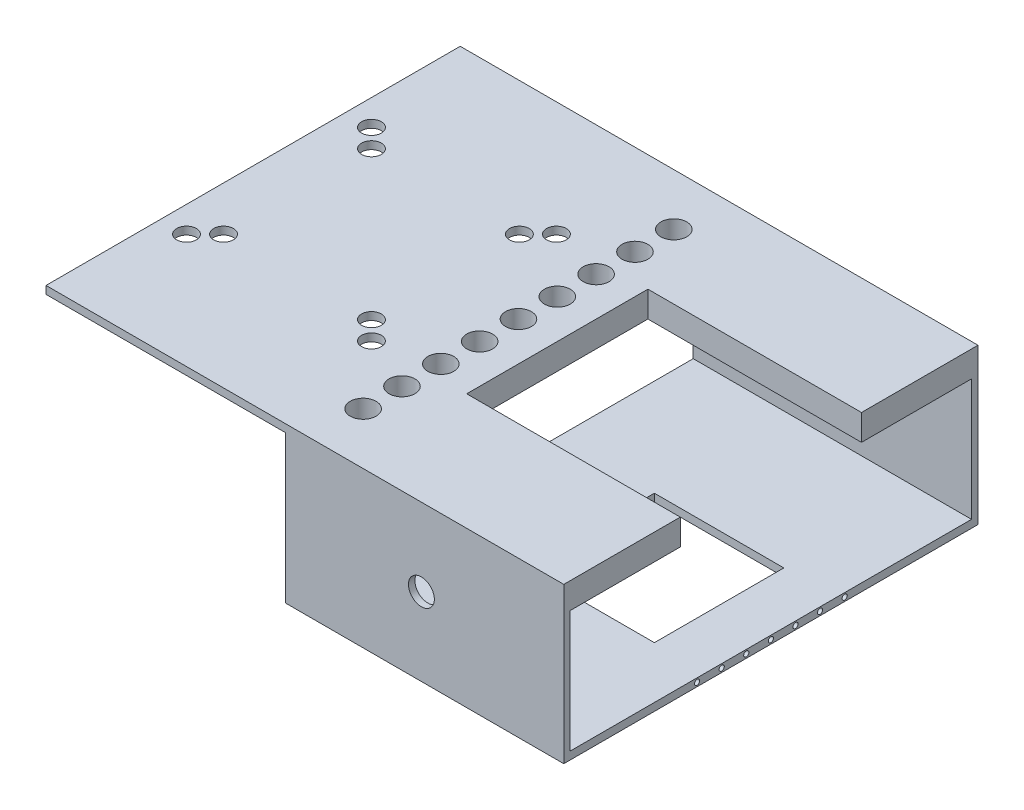
SolidWorks part; units mm, degrees
material "6063-T6"
ref_plane "前视基准面" through (0, 0, 0) normal (0, 0, 1) x (1, 0, 0)
ref_plane "上视基准面" through (0, 0, 0) normal (0, 1, 0) x (1, 0, 0)
ref_plane "右视基准面" through (0, 0, 0) normal (1, 0, 0) x (0, 0, -1)
other "Configuration Table"
sketch "草图1" plane through (0, 0, 0) normal (0, 1, 0) x (1, 0, 0)
  line L7 (-200, 160) -> (200, 160)
  line L8 (-200, 160) -> (-200, -160)
  line L9 (-200, -160) -> (200, -160)
  line L10 (200, 160) -> (200, -160)
extrude "凸台-拉伸7" add sketch "草图1" along normal blind 120
sketch "草图6" plane through (0, 120, 0) normal (0, 1, 0) x (1, 0, 0)
  circle A0 centre (-180, -71.4375) radius 7.62
  circle A1 centre (-165.7125, 57.1733) radius 7.62
  circle A2 centre (-165.7125, -57.1267) radius 7.62
  circle A3 centre (-180, 71.4375) radius 7.62
  circle A4 centre (-37.125, 71.4375) radius 7.62
  circle A5 centre (-51.4125, 57.1267) radius 7.62
  circle A6 centre (-51.4125, -57.1733) radius 7.62
  circle A7 centre (-37.125, -71.4375) radius 7.62
  dimension "D1" = 142.875
  dimension "D2" = 142.875
  dimension "D3" = 142.875
  dimension "D4" = 142.875
  dimension "D5" = 114.3
  dimension "D6" = 114.3
  dimension "D7" = 114.3
  dimension "D8" = 114.3
extrude "切除-拉伸3" cut sketch "草图6" against normal through all from surface at 0 contours A1 | A3 | A0 | A6 | A2 | A7 | A5 | A4 starting at face at (0, 120, 0)
sketch "草图7" plane through (0, 120, 0) normal (0, 1, 0) x (1, 0, 0)
  line L0 (-200, -160) -> (200, -160) construction
  line L1 (-200, 160) -> (-15, 160)
  line L2 (-200, 160) -> (-200, -160)
  line L3 (-200, -160) -> (-15, -160)
  line L4 (-15, 160) -> (-15, -160)
extrude "切除-拉伸4" cut sketch "草图7" along normal blind 114 from vertex at -120 starting at point (-200, 0, 160)
sketch "草图8" plane through (200, 0, 0) normal (1, 0, 0) x (0, 0, -1)
  line L1 (-155, 100) -> (155, 100)
  line L2 (-155, 100) -> (-155, 6)
  line L3 (-155, 6) -> (155, 6)
  line L4 (155, 100) -> (155, 6)
extrude "切除-拉伸5" cut sketch "草图8" against normal through all
sketch "草图10" plane through (0, 0, 160) normal (0, 0, 1) x (1, 0, 0)
  circle A0 centre (90, 60) radius 10
extrude "切除-拉伸7" cut sketch "草图10" against normal through all
sketch "草图12" plane through (0, 120, 0) normal (0, 1, 0) x (1, 0, 0)
  circle A0 centre (5, 90) radius 10
  circle A1 centre (5, 0) radius 10
  circle A2 centre (5, 30) radius 10
  circle A3 centre (5, 60) radius 10
  circle A4 centre (5, -30) radius 10
  circle A5 centre (5, -60) radius 10
  circle A6 centre (5, -90) radius 10
  circle A7 centre (5, 120) radius 10
  circle A8 centre (5, -120) radius 10
extrude "切除-拉伸8" cut sketch "草图12" against normal up to next
scale "缩放比例1" scale about centroid uniform scaling yes scale factor 1
sketch "草图13" plane through (200, 0, 0) normal (1, 0, 0) x (0, 0, -1)
  circle A0 centre (0, 3) radius 2
  circle A1 centre (19, 3) radius 2
  circle A2 centre (38, 3) radius 2
  circle A3 centre (57, 3) radius 2
  circle A4 centre (-57, 3) radius 2
  circle A5 centre (-38, 3) radius 2
  circle A6 centre (-19, 3) radius 2
extrude "切除-拉伸9" cut sketch "草图13" against normal blind 20
sketch "草图14" plane through (0, 6, 0) normal (0, 1, 0) x (1, 0, 0)
  line L1 (160, 50) -> (60, 50)
  line L2 (160, 50) -> (160, -50)
  line L3 (160, -50) -> (60, -50)
  line L4 (60, 50) -> (60, -50)
extrude "切除-拉伸12" cut sketch "草图14" against normal through all both and the other way through all
sketch "草图15" plane through (0, 120, 0) normal (0, 1, 0) x (1, 0, 0)
  line L0 (200, -160) -> (200, 160) construction
  line L1 (35, 70) -> (200, 70)
  line L2 (35, 70) -> (35, -70)
  line L3 (35, -70) -> (200, -70)
  line L4 (200, 70) -> (200, -70)
  point P6 (0, 0)
  point P7 (0, 0)
  point P8 (0, 0)
extrude "切除-拉伸13" cut sketch "草图15" against normal up to next
